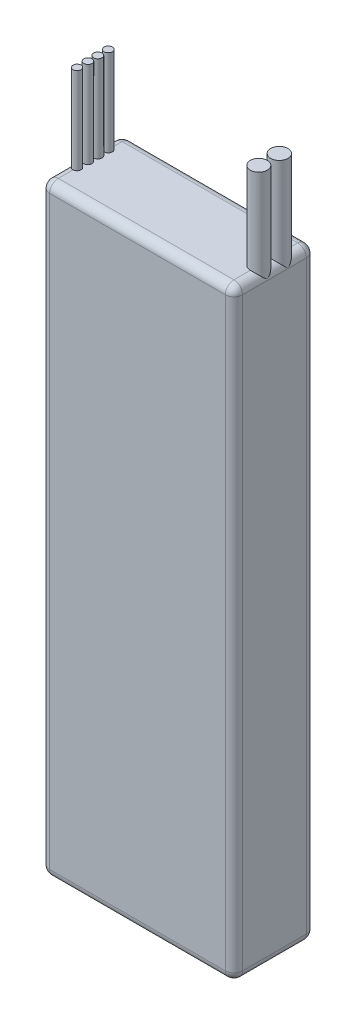
SolidWorks part; units mm, degrees
ref_plane "Front Plane" through (0, 0, 0) normal (0, 0, 1) x (1, 0, 0)
ref_plane "Top Plane" through (0, 0, 0) normal (0, 1, 0) x (1, 0, 0)
ref_plane "Right Plane" through (0, 0, 0) normal (1, 0, 0) x (0, 0, -1)
sketch "Sketch1" plane through (0, 0, 0) normal (0, 1, 0) x (1, 0, 0)
  line L1 (0, 18.7) -> (44.5, 18.7)
  line L2 (0, 18.7) -> (0, 0)
  line L3 (0, 0) -> (44.5, 0)
  line L4 (44.5, 18.7) -> (44.5, 0)
  dimension "D1" = 18.7
  dimension "D2" = 44.5
extrude "Boss-Extrude1" add sketch "Sketch1" along normal blind 139
fillet "Fillet1" radius 2 12 edges at (22.25, 0, -18.7) (0, 69.5, -18.7) (0, 0, -9.35) (22.25, 139, -18.7) (0, 139, -9.35) (44.5, 139, -9.35) (44.5, 69.5, -18.7) (44.5, 0, -9.35) (0, 69.5, 0) (22.25, 139, 0) (44.5, 69.5, 0) (22.25, 0, 0)
sketch "Sketch2" plane through (0, 139, 0) normal (0, 1, 0) x (1, 0, 0)
  line L2 (42.5, 2) -> (42.5, 16.7) construction
  line L3 (2, 16.7) -> (2, 2) construction
  circle A0 centre (42.5, 7.7313) radius 1.96
  circle A1 centre (42.5, 12.4677) radius 1.9883
  circle A2 centre (2, 6.3279) radius 0.9186
  circle A3 centre (2, 11.1081) radius 0.9712
  circle A4 centre (2, 13.5202) radius 0.9539
  circle A5 centre (2, 8.8277) radius 0.951
extrude "Boss-Extrude2" add sketch "Sketch2" along normal blind 20 and the other way up to next
